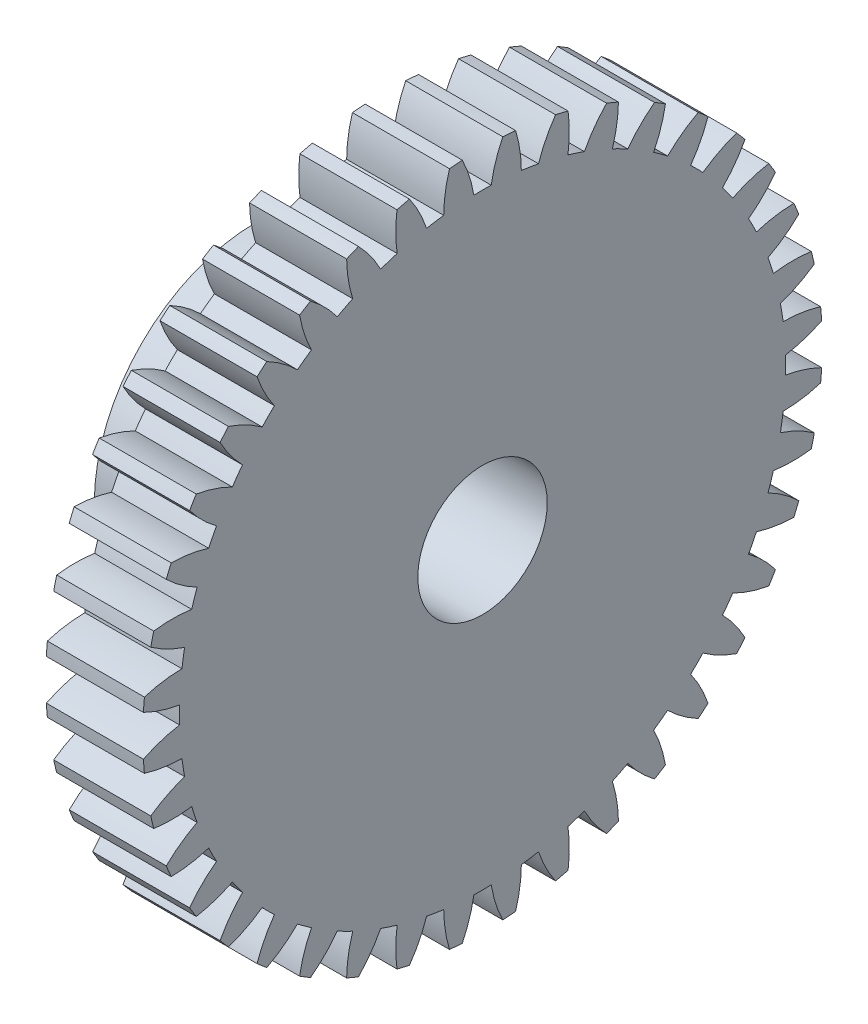
SolidWorks part; units mm, degrees
ref_plane "Plane1" through (0, 0, 0) normal (0, 0, 1) x (1, 0, 0)
ref_plane "Plane2" through (0, 0, 0) normal (0, 1, 0) x (1, 0, 0)
ref_plane "Plane3" through (0, 0, 0) normal (1, 0, 0) x (0, 0, -1)
sketch "BasProSke" plane through (0, 0, 0) normal (0, 1, 0) x (1, 0, 0)
  line L0 (-10, 0) -> (60, 0) construction
  line L1 (0, 0) -> (0, 16.6687)
  line L2 (0, 0) -> (4.7625, 0)
  line L3 (4.7625, 0) -> (4.7625, 16.6688)
  line L4 (4.7625, 16.6688) -> (0, 16.6687)
  dimension "Diameter" = 33.3375
  dimension "Thickness" = 4.7625
revolve "Base-Revolve" add sketch "BasProSke" angle 360 about L0
sketch "TooCutSke" plane through (0, 0, 0) normal (1, 0, 0) x (0, 0, -1)
  line L1 (0, 0) -> (0, 107) construction
  line L2 (0, 0) -> (-0.673, 15.8607) construction
  line L3 (0, 0) -> (-2.4895, 31.6315) construction
  line L4 (-0.673, 15.8607) -> (-1.2447, 15.8157) construction
  arc A0 (0.4256, 14.8656) -> (-0.4256, 14.8656) centre (0, 0) ccw
  arc A1 (1.006, 16.6638) -> (-1.006, 16.6638) centre (0, 0) ccw
  circle A2 centre (0, 0) radius 15.875 construction
  circle A3 centre (0, 0) radius 15.3693 construction
  arc A4 (-0.4256, 14.8656) -> (-1.006, 16.6638) centre (-6.6916, 13.8361) ccw
  arc A5 (1.006, 16.6638) -> (0.4256, 14.8656) centre (6.6916, 13.8361) ccw
  dimension "Root_dia" = 29.7434
  dimension "Overcut_dia" = 33.3883
  dimension "Pitch_dia" = 31.75
  dimension "Base_dia" = 30.7387
  dimension "Flank_rad" = 6.35
  dimension "Half_ang" = 4.5
  dimension "Half_CT" = 0.5735
extrude "ToothCut" cut sketch "TooCutSke" along normal through all
pattern_circular "TeethCuts" count 40 every 9 about axis through (-10, 0, 0) along (1, 0, 0) of "ToothCut"
sketch "HubNeaOneSke" plane through (4.7625, 0, 0) normal (-1, 0, 0) x (0, 0, 1)
  circle A0 centre (0, 0) radius 7.9375
  dimension "Diameter" = 15.875
extrude "HubNearOne" add sketch "HubNeaOneSke" along normal blind 11.1125
sketch "BorSke" plane through (4.7625, 0, 0) normal (1, 0, 0) x (0, 0, -1)
  circle A0 centre (0, 0) radius 3.175
  dimension "Diameter" = 6.35
extrude "Bore" cut sketch "BorSke" against normal through all
equation "\"Num_teeth@TeethCuts\" = ((sgn( \"Num_teeth@TeethCuts\" - 2.0)+1)*( \"Num_teeth@TeethCuts\" - 2.0))/2 +2.0"
